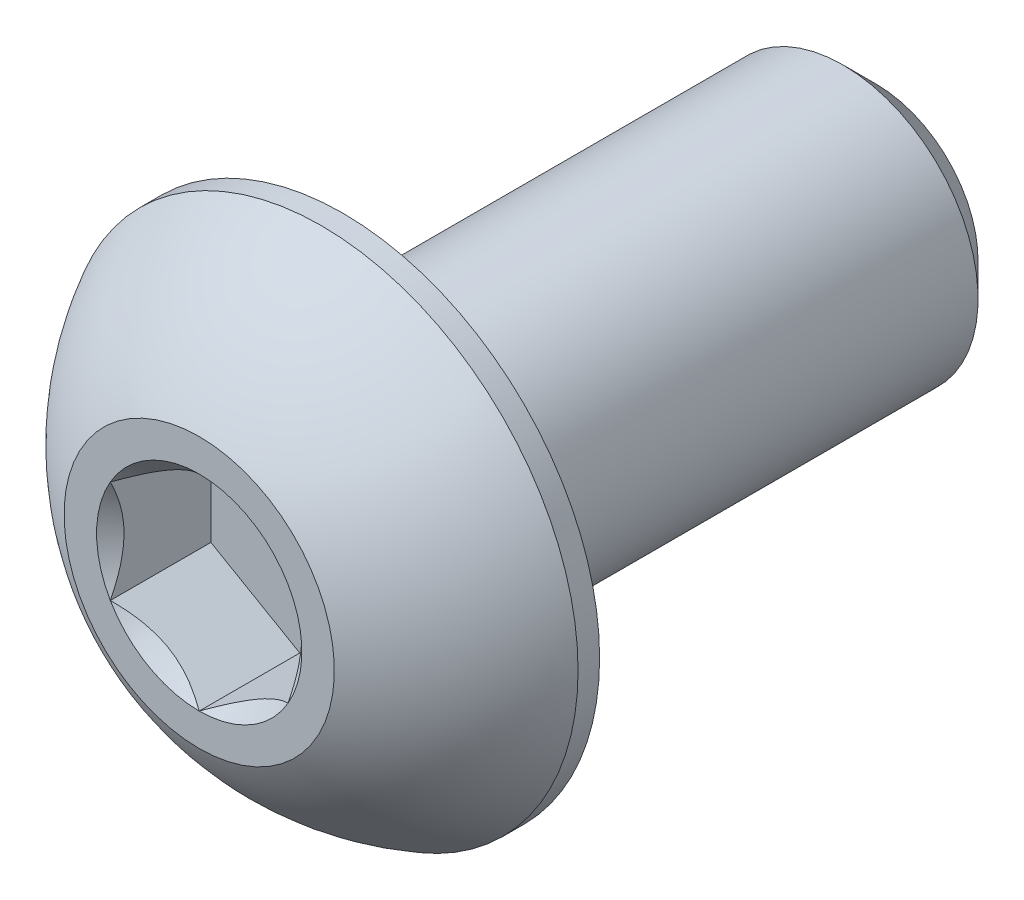
SolidWorks part; units mm, degrees
material "AISI 4130 Steel, annealed at 865C"
ref_plane "Front" through (0, 0, 0) normal (0, 0, 1) x (1, 0, 0)
ref_plane "Top" through (0, 0, 0) normal (0, 1, 0) x (1, 0, 0)
ref_plane "Right" through (0, 0, 0) normal (1, 0, 0) x (0, 0, -1)
sketch "Sketch1" plane through (0, 0, 0) normal (1, 0, 0) x (0, 0, -1)
  line L2 (2.5654, 2.413) -> (12.0904, 2.413)
  line L3 (12.0904, 2.413) -> (12.0904, 0)
  line L4 (12.0904, 0) -> (2.5654, 0)
  line L6 (2.1806, 4.5847) -> (2.5654, 4.5847) construction
  line L7 (12.0904, 2.413) -> (12.0904, -2.413) construction
  line L8 (0, 0) -> (2.5654, 0) construction
  line L9 (2.5654, 4.5847) -> (2.5654, -4.5847) construction
  line L11 (2.5654, 2.413) -> (2.5654, 0)
  line L13 (0, 1.5875) -> (0, -1.5875) construction
  line L14 (0, 1.5875) -> (0, 2.413) construction
  arc A3 (0, 2.413) -> (2.1806, 4.5847) centre (4.5749, 0) cw construction
  dimension "D1" = 0.3848
revolve "Revolve1" add sketch "Sketch1" angle 360 mid plane about L4
sketch "Sketch3" plane through (0, 0, -12.0904) normal (0, 0, -1) x (-1, 0, 0)
  circle A0 centre (0, 0) radius 2.413
curve "Helix/Spiral1" pitch 0.7937 height 10.3188 turns 13
sketch "Sketch2" plane through (0, 0, 0) normal (1, 0, 0) x (0, 0, -1)
  line L0 (12.0904, 2.413) -> (12.7849, 2.413)
  line L1 (12.7849, 2.413) -> (12.4873, 1.8974)
  line L2 (12.4873, 1.8974) -> (12.3881, 1.8974)
  line L3 (12.3881, 1.8974) -> (12.0904, 2.413)
  line L4 (12.2392, 2.1552) -> (12.6361, 2.1552) construction
  dimension "D1" = 60
  dimension "D2" = 0.0992
  dimension "D3" = 0.3969
chamfer "Chamfer1" distance 0.5953 angle 45 1 edges at (0, 2.413, -12.0904)
sketch "Sketch7" plane through (0, 0, 0) normal (1, 0, 0) x (0, 0, -1)
  line L6 (2.1806, 4.5847) -> (2.5654, 4.5847) construction
  line L8 (0, 0) -> (2.5654, 0) construction
  line L11 (2.5654, 4.5847) -> (2.5654, -4.5847) construction
  line L12 (2.1806, 4.5847) -> (2.5654, 4.5847)
  line L13 (0, 0) -> (2.5654, 0)
  line L14 (0, 1.5875) -> (0, -1.5875) construction
  line L15 (2.5654, 4.5847) -> (2.5654, 0)
  line L16 (0, 2.413) -> (0, 0)
  arc A2 (2.1806, 4.5847) -> (0, 2.413) centre (4.5749, 0) ccw construction
  arc A3 (2.1806, 4.5847) -> (0, 2.413) centre (4.5749, 0) ccw
revolve "Revolve2" add sketch "Sketch7" angle 360 mid plane about L13
sketch "Sketch5" plane through (0, 0, 0) normal (0, 0, 1) x (1, 0, 0)
  line L1 (1.5875, -0.9165) -> (1.5875, 0.9165)
  line L2 (1.5875, 0.9165) -> (0, 1.8331)
  line L3 (0, 1.8331) -> (-1.5875, 0.9165)
  line L4 (-1.5875, 0.9165) -> (-1.5875, -0.9165)
  line L5 (-1.5875, -0.9165) -> (0, -1.8331)
  line L6 (0, -1.8331) -> (1.5875, -0.9165)
  circle A0 centre (0, 0) radius 1.5875 construction
extrude "Cut-Extrude2" cut sketch "Sketch5" against normal blind 1.7958
sketch "Sketch6" plane through (0, 0, 0) normal (0, 0, 1) x (1, 0, 0)
  circle A0 centre (0, 0) radius 1.8331
extrude "Cut-Extrude3" cut sketch "Sketch6" against normal blind 1.7958 draft 45
sketch "Sketch10" plane through (0, 0, 0) normal (1, 0, 0) x (0, 0, -1)
  line L0 (12.0904, 2.413) -> (12.0904, -2.413) construction
  point P0 (10.8998, -2.413)
  dimension "D1" = 1.1906
equation "\"D3@Helix/Spiral1\" = \"Lg@Sketch1\" + \"D4@Helix/Spiral1\""
equation "\"D2@Sketch2\" = \"D4@Helix/Spiral1\" * .125"
equation "\"D3@Sketch2\" = \"D4@Helix/Spiral1\" * .5"
equation "\"D1@Chamfer1\" = \"D4@Helix/Spiral1\" * .75"
equation "\"D1@Cut-Extrude2\" = \"Head Ht@Sketch1\" * .7"
equation "\"D1@Sketch1\" = \"Head Ht@Sketch1\" * .15"
equation "\"D1@Sketch10\" = \"D4@Helix/Spiral1\" * 1.5"
equation "\"D1@Cut-Extrude3\" = \"D1@Cut-Extrude2\""
